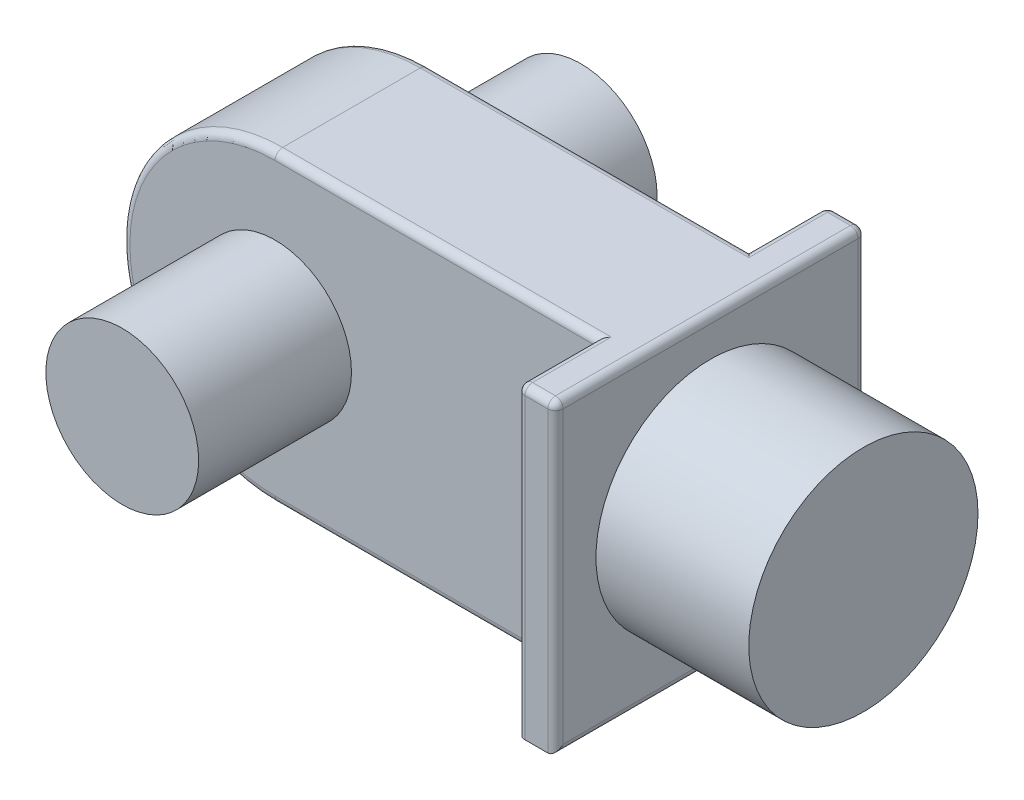
SolidWorks part; units mm, degrees
ref_plane "Front Plane" through (0, 0, 0) normal (0, 0, 1) x (1, 0, 0)
ref_plane "Top Plane" through (0, 0, 0) normal (0, 1, 0) x (1, 0, 0)
ref_plane "Right Plane" through (0, 0, 0) normal (1, 0, 0) x (0, 0, -1)
sketch "Sketch1" plane through (0, 0, 0) normal (0, 0, 1) x (1, 0, 0)
  line L1 (-42, 20) -> (0, 20)
  line L2 (-42, -20) -> (0, -20)
  line L3 (0, -20) -> (0, 20)
  arc A0 (-42, 20) -> (-42, -20) centre (-42, 0) ccw
  dimension "D2" = 40
extrude "Boss-Extrude1" add sketch "Sketch1" along normal blind 20
sketch "Sketch2" plane through (0, 0, 20) normal (0, 0, 1) x (1, 0, 0)
  circle A0 centre (-42, 0) radius 10
  dimension "D1" = 20
extrude "Boss-Extrude2" add sketch "Sketch2" along normal blind 20
ref_plane "Plane1" through (0, 0, 10) normal (0, 0, 1) x (1, 0, 0)
mirror "Mirror1" about plane through (0, 0, 10) normal (0, 0, 1) of "Boss-Extrude2"
sketch "Sketch3" plane through (0, 0, 0) normal (1, 0, 0) x (0, 0, -1)
  line L0 (-20, 0) -> (0, 0) construction
  line L1 (-20, -20) -> (-20, 20) construction
  line L2 (-10, 20) -> (-10, -20) construction
  line L3 (-20, 20) -> (0, 20) construction
  line L4 (-20, -20) -> (0, -20) construction
  line L6 (-30.299, 20) -> (10.299, 20)
  line L7 (-30.299, 20) -> (-30.299, -20)
  line L8 (-30.299, -20) -> (10.299, -20)
  line L9 (10.299, 20) -> (10.299, -20)
  point P11 (-10, 0)
extrude "Boss-Extrude3" add sketch "Sketch3" along normal blind 5
sketch "Sketch4" plane through (5, 0, 0) normal (1, 0, 0) x (0, 0, -1)
  line L0 (-30.299, 20) -> (10.299, -20) construction
  line L2 (10.299, 20) -> (-30.299, -20) construction
  circle A0 centre (-10, 0) radius 15
  dimension "D1" = 30
extrude "Boss-Extrude4" add sketch "Sketch4" along normal blind 20
fillet "Fillet1" radius 1 16 edges at (-21, -20, 20) (-62, 0, 20) (-21, -20, 0) (-62, 0, 0) (0, 20, -5.1495) (2.5, 20, -10.299) (5, 20, 10) (2.5, 20, 30.299) (0, 20, 25.1495) (-21, 20, 20) (-21, 20, 0) (5, 0, 30.299) (5, 0, -10.299) (5, -20, 10) (0, 0, 30.299) (0, 0, -10.299)
scale "Ölçek2" bodies to scale 105 scale about centroid uniform scaling yes scale factor 0.2
